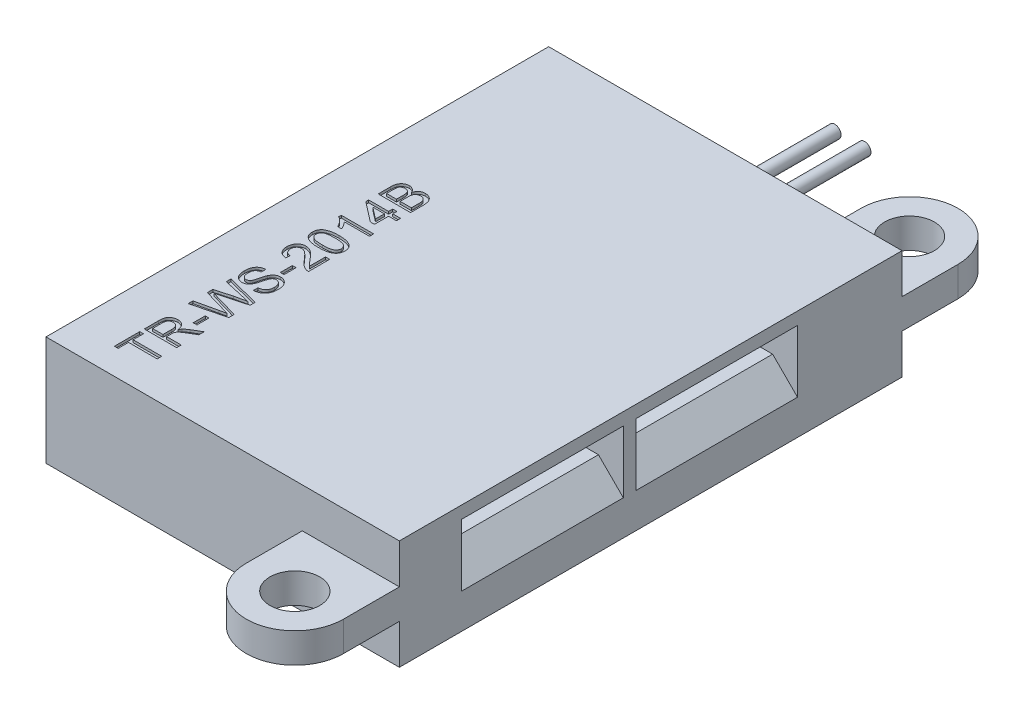
SolidWorks part; units mm, degrees
material "ABS"
ref_plane "Front Plane" through (0, 0, 0) normal (0, 0, 1) x (1, 0, 0)
ref_plane "Top Plane" through (0, 0, 0) normal (0, 1, 0) x (1, 0, 0)
ref_plane "Right Plane" through (0, 0, 0) normal (1, 0, 0) x (0, 0, -1)
sketch "Sketch1" plane through (0, 0, 0) normal (0, 1, 0) x (1, 0, 0)
  line L1 (-7.1, 10.1) -> (7.1, 10.1)
  line L2 (-7.1, 10.1) -> (-7.1, -10.1)
  line L3 (-7.1, -10.1) -> (7.1, -10.1)
  line L4 (7.1, 10.1) -> (7.1, -10.1)
  line L5 (0, -10.1) -> (0, 10.1) construction
  line L6 (-7.1, 0) -> (7.1, 0) construction
  point P0 (0, 0)
  dimension "D1" = 14.2
  dimension "D2" = 20.2
extrude "Boss-Extrude1" add sketch "Sketch1" along normal blind 4.4
ref_plane "Plane1" through (0, 2.2, 0) normal (0, 1, 0) x (1, 0, 0)
sketch "Sketch2" plane through (0, 2.2, 0) normal (0, 1, 0) x (1, 0, 0)
  line L0 (3.2, 10.1) -> (3.2, 12.35)
  line L1 (-7.1, 10.1) -> (7.1, 10.1) construction
  line L2 (7.1, 12.35) -> (7.1, 10.1)
  line L3 (3.2, 10.1) -> (7.1, 10.1)
  arc A0 (3.2, 12.35) -> (7.1, 12.35) centre (5.15, 12.35) cw
  circle A1 centre (5.15, 12.35) radius 1
  point P9 (5.15, 14.3)
  dimension "D1" = 4.2
  dimension "D3" = 2
  dimension "D2" = 3.9
extrude "Boss-Extrude2" add sketch "Sketch2" along normal mid plane 1.2
mirror "Mirror1" about plane through (0, 0, 0) normal (0, 0, 1) of "Boss-Extrude2"
sketch "Sketch3" plane through (7.1, 0, 0) normal (1, 0, 0) x (0, 0, -1)
  line L0 (-10.1, 4.4) -> (-10.1, 2.8) construction
  line L1 (-7.6, 3.9) -> (-1.1, 3.9)
  line L2 (-7.6, 3.9) -> (-7.6, 2.4)
  line L3 (-7.6, 2.4) -> (-1.1, 2.4)
  line L4 (-1.1, 3.9) -> (-1.1, 2.4)
  line L5 (-10.1, 4.4) -> (10.1, 4.4) construction
  dimension "D1" = 2.5
  dimension "D2" = 0.5
  dimension "D3" = 1.5
  dimension "D4" = 6.5
extrude "Cut-Extrude1" cut sketch "Sketch3" against normal blind 8
chamfer "Chamfer1" distance 1 angle 45 1 edges at (7.1, 2.4, 4.35)
pattern_linear "LPattern1" count 2 spacing 7 along (0, 0, -1) of "Cut-Extrude1", "Chamfer1"
sketch "Sketch4" plane through (0, 4.4, 0) normal (0, 1, 0) x (1, 0, 0)
  line L0 (-4.1, -9.1) -> (-4.1, 10.1) construction
  line L2 (7.1, 10.1) -> (-7.1, 10.1) construction
  line L3 (-7.1, -10.1) -> (7.1, -10.1) construction
  line L4 (-7.1, 10.1) -> (-7.1, -10.1) construction
  text T0 "TR-WS-2014B" font "Arial" height 1.3
  point P3 (-4.4856, -10.1)
  point P4 (-4.5229, -8.9533)
  point P6 (-4.3228, 10.1)
  dimension "D1" = 1
  dimension "D2" = 3
extrude "Cut-Extrude2" cut sketch "Sketch4" against normal blind 0.1
sketch "Sketch5" plane through (0, 0, -10.1) normal (0, 0, -1) x (-1, 0, 0)
  line L0 (7.81, 2.2) -> (-7.81, 2.2) construction
  line L1 (0, 2.42) -> (0, -2.42) construction
  circle A1 centre (0.6, 2.2) radius 0.25
  dimension "D1" = 0.5
  dimension "D2" = 0.6
extrude "Boss-Extrude3" add sketch "Sketch5" along normal blind 5 separate body
mirror "Mirror3" about plane through (0, 0, 0) normal (1, 0, 0) of bodies 109
